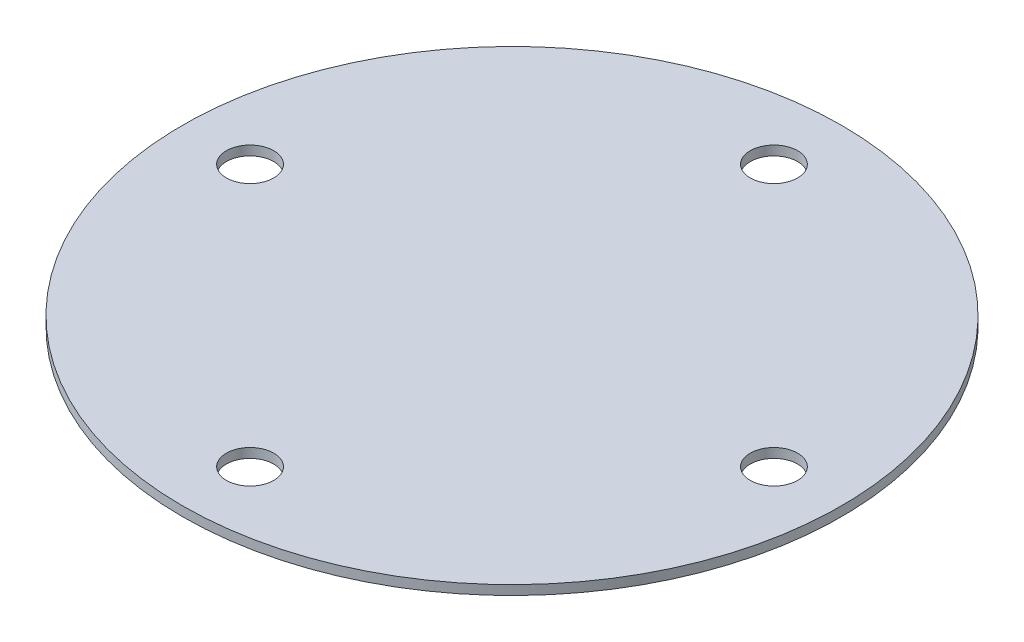
SolidWorks part; units mm, degrees
ref_plane "Front Plane" through (0, 0, 0) normal (0, 0, 1) x (1, 0, 0)
ref_plane "Top Plane" through (0, 0, 0) normal (0, 1, 0) x (1, 0, 0)
ref_plane "Right Plane" through (0, 0, 0) normal (1, 0, 0) x (0, 0, -1)
sketch "Sketch1" plane through (0, 0, 0) normal (0, 1, 0) x (1, 0, 0)
  circle A0 centre (0, 0) radius 88.519
extrude "Boss-Extrude1" add sketch "Sketch1" along normal blind 2.54
sketch "Sketch2" plane through (0, 2.54, 0) normal (0, 1, 0) x (1, 0, 0)
  circle A0 centre (0, 70.358) radius 6.35
  circle A1 centre (70.358, 0) radius 6.35
  circle A2 centre (0, -70.358) radius 6.35
  circle A3 centre (-70.358, 0) radius 6.35
  point P12 (0, 0)
  dimension "D1" = 70.358
  dimension "D2" = 4
extrude "Cut-Extrude1" cut sketch "Sketch2" against normal through all
